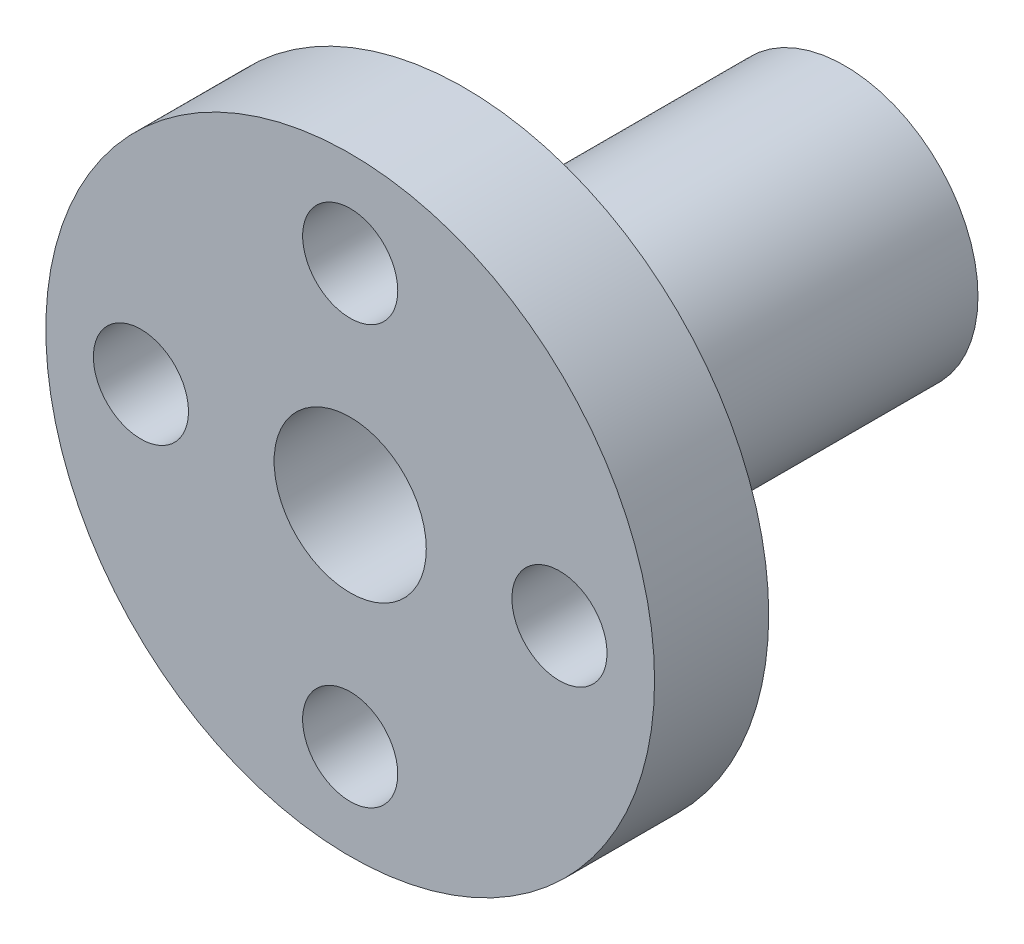
SolidWorks part; units mm, degrees
ref_plane "Front Plane" through (0, 0, 0) normal (0, 0, 1) x (1, 0, 0)
ref_plane "Top Plane" through (0, 0, 0) normal (0, 1, 0) x (1, 0, 0)
ref_plane "Right Plane" through (0, 0, 0) normal (1, 0, 0) x (0, 0, -1)
sketch "Sketch1" plane through (0, 0, 0) normal (0, 0, 1) x (1, 0, 0)
  circle A0 centre (0, 0) radius 8
  circle A1 centre (0, 0) radius 5.5 construction
  circle A2 centre (0, 5.5) radius 1.25
  circle A3 centre (5.5, 0) radius 1.25
  circle A4 centre (0, -5.5) radius 1.25
  circle A5 centre (-5.5, 0) radius 1.25
  dimension "D1" = 2.5
  dimension "D2" = 11
  dimension "D3" = 16
extrude "Boss-Extrude1" add sketch "Sketch1" along normal blind 3
sketch "Sketch2" plane through (0, 0, 0) normal (0, 0, 1) x (1, 0, 0)
  circle A0 centre (0, 0) radius 3.5
  dimension "D1" = 7
extrude "Boss-Extrude2" add sketch "Sketch2" against normal blind 10
sketch "Sketch3" plane through (0, 0, 3) normal (0, 0, 1) x (1, 0, 0)
  circle A0 centre (0, 0) radius 2
  dimension "D1" = 4
extrude "Cut-Extrude1" cut sketch "Sketch3" against normal through all
